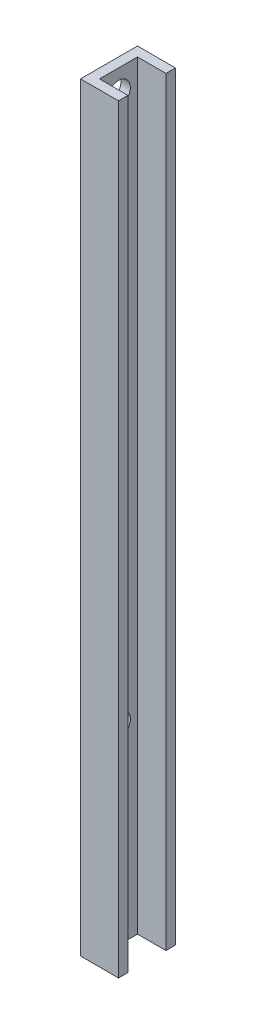
SolidWorks part; units mm, degrees
ref_plane "Front Plane" through (0, 0, 0) normal (0, 0, 1) x (1, 0, 0)
ref_plane "Top Plane" through (0, 0, 0) normal (0, 1, 0) x (1, 0, 0)
ref_plane "Right Plane" through (0, 0, 0) normal (1, 0, 0) x (0, 0, -1)
sketch "Sketch1" plane through (0, 0, 0) normal (0, 1, 0) x (1, 0, 0)
  line L0 (0, 0) -> (12.7, 0)
  line L1 (12.7, 0) -> (12.7, 3.175)
  line L2 (12.7, 3.175) -> (3.175, 3.175)
  line L3 (3.175, 3.175) -> (3.175, 15.875)
  line L4 (3.175, 15.875) -> (12.7, 15.875)
  line L5 (12.7, 15.875) -> (12.7, 19.05)
  line L6 (12.7, 19.05) -> (0, 19.05)
  line L7 (0, 19.05) -> (0, 0)
  dimension "D1" = 19.05
  dimension "D2" = 3.175
  dimension "D3" = 3.175
  dimension "D4" = 12.7
  dimension "D5" = 12.7
  dimension "D6" = 9.525
extrude "Boss-Extrude1" add sketch "Sketch1" along normal blind 254
sketch "Sketch5" plane through (3.175, 0, 0) normal (1, 0, 0) x (0, 0, -1)
  line L0 (3.175, 0) -> (15.875, 0) construction
  line L1 (19.05, 254) -> (19.05, 0) construction
  line L2 (3.175, 254) -> (15.875, 254) construction
  line L3 (0, 254) -> (0, 0) construction
  circle A0 centre (9.525, 63.5) radius 3.9688
  circle A1 centre (9.525, 246.38) radius 3.9687
  point P10 (9.525, 254)
  dimension "D1" = 7.9375
  dimension "D5" = 7.62
  dimension "D6" = 7.9375
  dimension "D2" = 63.5
  dimension "D3" = 9.525
  dimension "D4" = 9.525
extrude "Cut-Extrude1" cut sketch "Sketch5" against normal blind 12.7
